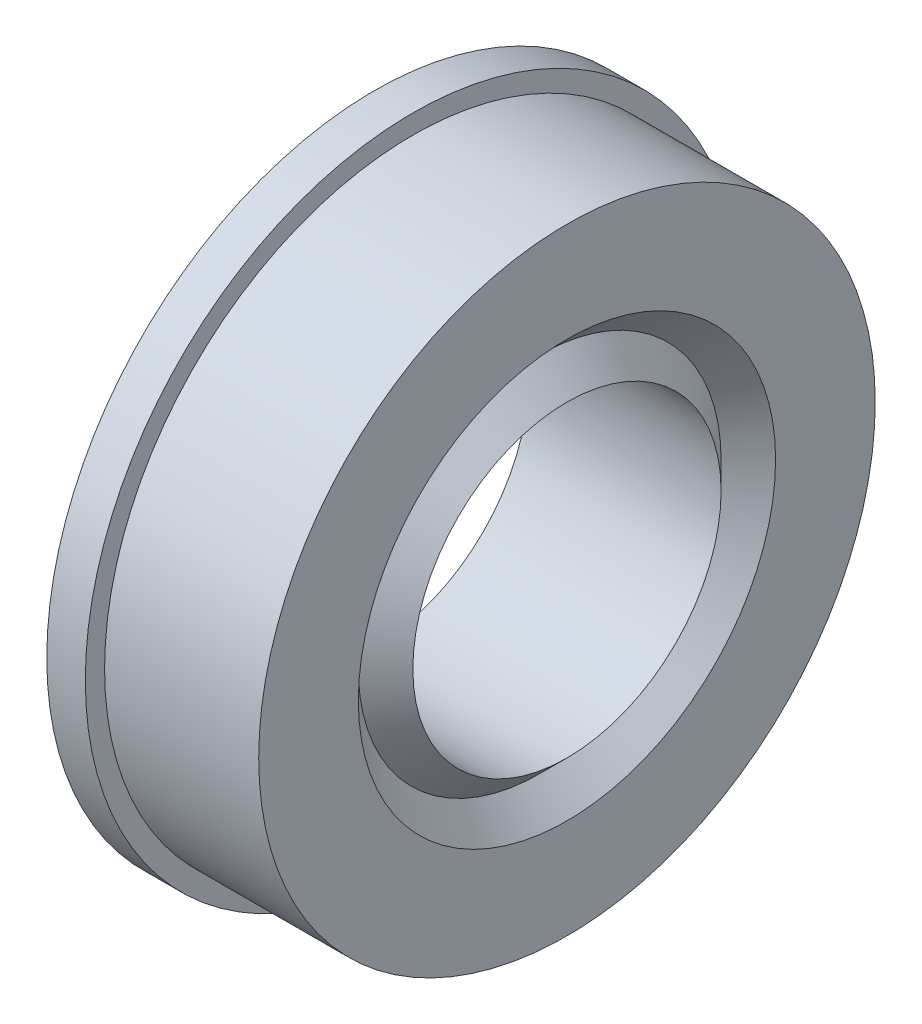
SolidWorks part; units mm, degrees
ref_plane "前视基准面" through (0, 0, 0) normal (0, 0, 1) x (1, 0, 0)
ref_plane "上视基准面" through (0, 0, 0) normal (0, 1, 0) x (1, 0, 0)
ref_plane "右视基准面" through (0, 0, 0) normal (1, 0, 0) x (0, 0, -1)
sketch "草图1" plane through (0, 0, 0) normal (0, 1, 0) x (1, 0, 0)
  line L0 (-5, -4) -> (0, -4)
  line L1 (0, 0) -> (-5, 0)
  line L2 (0, 0) -> (0, -8)
  line L3 (0, -8) -> (-5, -8)
  line L4 (-5, 0) -> (-5, -8)
  line L5 (-5, -8) -> (-4.2929, -7.2929)
  line L6 (-4.2929, -7.2929) -> (-5, -6.5858)
  line L7 (-5, -6.5858) -> (-5, -5.4142)
  line L8 (-5, -5.4142) -> (-4.2929, -4.7071)
  line L9 (-4.2929, -4.7071) -> (-5, -4)
  line L10 (0, -8) -> (0.7929, -8.7929)
  line L11 (0.7929, -8.7929) -> (0, -9.5858)
  line L12 (0, -5.4142) -> (-0.7071, -4.7071)
  line L13 (-0.7071, -4.7071) -> (0, -4)
  dimension "D1" = 5
  dimension "D2" = 8
  dimension "D3" = 4
  dimension "D4" = 1
  dimension "D5" = 90
  dimension "D6" = 1
revolve "旋转1" add sketch "草图1" angle 360 about L1
sketch "草图2" plane through (-5, 0, 0) normal (-1, 0, 0) x (0, 0, 1)
  circle A0 centre (0, 0) radius 8.5
  circle A1 centre (0, 0) radius 8
  dimension "D1" = 0.5
  dimension "D2" = 17
extrude "凸台-拉伸1" add sketch "草图2" against normal blind 1 separate body
